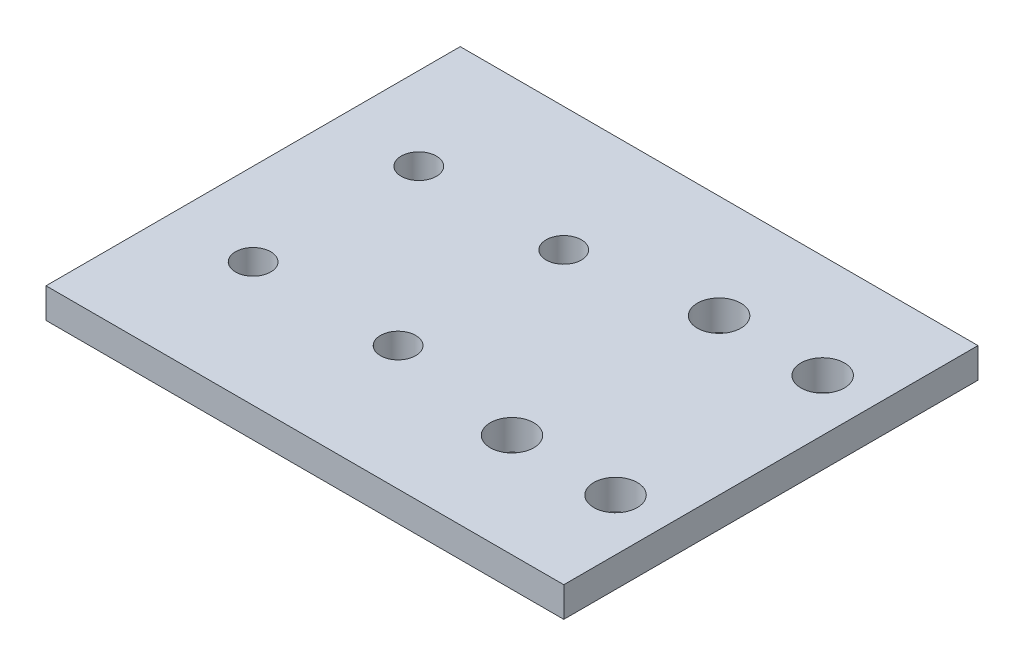
SolidWorks part; units mm, degrees
ref_plane "前视基准面" through (0, 0, 0) normal (0, 0, 1) x (1, 0, 0)
ref_plane "上视基准面" through (0, 0, 0) normal (0, 1, 0) x (1, 0, 0)
ref_plane "右视基准面" through (0, 0, 0) normal (1, 0, 0) x (0, 0, -1)
other "Configuration Table"
sketch "草图1" plane through (0, 0, 0) normal (0, 1, 0) x (1, 0, 0)
  line L0 (0, 120) -> (0, -49880) construction
  line L1 (-100, -120) -> (100, -120)
  line L2 (-100, -120) -> (-100, 120)
  line L3 (-100, 120) -> (100, 120)
  line L4 (100, -120) -> (100, 120)
  line L5 (-100, -120) -> (100, 120) construction
  line L6 (-100, 120) -> (100, -120) construction
  line L7 (-100, 120) -> (-70, 120)
  line L8 (-100, 120) -> (-100, 80)
  line L9 (-100, 80) -> (-70, 80)
  line L10 (-70, 120) -> (-70, 80)
  line L11 (-65, 0) -> (49935, 0) construction
  line L12 (-70, 120) -> (-70, 113)
  line L13 (-70, 113) -> (-70, 87)
  line L14 (-70, 87) -> (-70, 80)
  line L15 (-70, 113) -> (-40, 113)
  line L16 (-40, 113) -> (-40, 87)
  line L17 (-40, 87) -> (-70, 87)
  line L18 (-70, 113) -> (-70, 108)
  line L19 (-70, 87) -> (-70, 92)
  line L20 (-40, 87) -> (-48, 87)
  line L21 (-48, 87) -> (-48, 92)
  line L22 (-48, 92) -> (-40, 92)
  line L23 (-70, 92) -> (-62, 92)
  line L24 (-62, 92) -> (-62, 87)
  line L25 (-70, 100) -> (-40, 100) construction
  line L26 (0, 120) -> (0, 0)
  line L27 (0, 0) -> (-100, 0)
  line L28 (-70, 80) -> (0, 80)
  line L29 (100, 80) -> (70, 80)
  line L30 (70, 120) -> (70, 80)
  line L31 (100, -80) -> (70, -80)
  line L32 (70, -120) -> (70, -80)
  line L33 (-70, -120) -> (-70, -80)
  line L34 (-100, -80) -> (-70, -80)
  line L35 (0, 120) -> (0, 100)
  line L36 (0, 100) -> (-25, 100)
  line L37 (-25, 100) -> (-25, 115)
  line L38 (-25, 100) -> (-25, 85)
  line L39 (-25, 85) -> (-5, 85)
  line L40 (-25, 115) -> (-5, 115)
  line L41 (-5, 115) -> (-5, 85)
  line L42 (5, 115) -> (5, 85)
  line L43 (25, 100) -> (25, 85)
  line L44 (25, 85) -> (5, 85)
  line L45 (25, 115) -> (5, 115)
  line L46 (25, 100) -> (25, 115)
  line L47 (25, -85) -> (5, -85)
  line L48 (25, -100) -> (25, -85)
  line L49 (25, -100) -> (25, -115)
  line L50 (25, -115) -> (5, -115)
  line L51 (5, -115) -> (5, -85)
  line L52 (-25, -100) -> (-25, -115)
  line L53 (-25, -100) -> (-25, -85)
  line L54 (-25, -85) -> (-5, -85)
  line L55 (-5, -115) -> (-5, -85)
  line L56 (-25, -115) -> (-5, -115)
  line L57 (-100, 0) -> (-90, 0)
  line L58 (0, 120) -> (0, 100)
  line L59 (0, 120) -> (0, 110)
  line L60 (-70, 80) -> (0, 80)
  line L61 (-70, 113) -> (-20, 113)
  line L62 (-70, 80) -> (0, 80)
  line L63 (-20, 113) -> (-40, 113)
  line L64 (-20, 113) -> (-20, 87)
  line L65 (-20, 87) -> (-40, 87)
  line L66 (-40, 113) -> (-40, 87)
  line L67 (-20, 87) -> (-20, 80)
  line L68 (-20, 80) -> (-20, 120)
  circle A0 centre (-62, 92) radius 1.7
  circle A1 centre (-48, 92) radius 1.7
  circle A2 centre (-48, 108) radius 1.7
  circle A3 centre (-62, 108) radius 1.7
  circle A4 centre (48, 108) radius 1.7
  circle A5 centre (48, 92) radius 1.7
  circle A6 centre (62, 92) radius 1.7
  circle A7 centre (62, 108) radius 1.7
  circle A8 centre (62, -108) radius 1.7
  circle A9 centre (62, -92) radius 1.7
  circle A10 centre (48, -92) radius 1.7
  circle A11 centre (48, -108) radius 1.7
  circle A12 centre (-48, -92) radius 1.7
  circle A13 centre (-62, -92) radius 1.7
  circle A14 centre (-48, -108) radius 1.7
  circle A15 centre (-62, -108) radius 1.7
  circle A16 centre (-90, 0) radius 2.5
  circle A17 centre (-90, 50) radius 2.5
  circle A18 centre (-90, -50) radius 2.5
  circle A19 centre (90, -50) radius 2.5
  circle A20 centre (90, 0) radius 2.5
  circle A21 centre (90, 50) radius 2.5
  circle A22 centre (0, 110) radius 2.5
  circle A23 centre (35, 110) radius 2.5
  point P0 (0, 0)
  point P11 (0, 120)
  point P14 (-100, 0)
  point P15 (100, 0)
  dimension "D12" = 3.4
  dimension "D13" = 3.4
  dimension "D19" = 5
  dimension "D23" = 5
  dimension "D1" = 200
  dimension "D2" = 240
  dimension "D3" = 30
  dimension "D4" = 40
  dimension "D5" = 7
  dimension "D6" = 7
  dimension "D7" = 30
  dimension "D8" = 5
  dimension "D9" = 5
  dimension "D10" = 8
  dimension "D11" = 8
  dimension "D14" = 25
  dimension "D15" = 15
  dimension "D16" = 15
  dimension "D17" = 20
  dimension "D18" = 10
  dimension "D21" = 20
  dimension "D22" = 10
  dimension "D25" = 50
  dimension "D26" = 40
  dimension "D20" = 2
  dimension "D24" = 2
extrude "凸台-拉伸3" add sketch "草图1" along normal blind 2.9 contours A1 L22 L16 L15 L10 L13 L23 A0 L24 L17 L21 A2 A3 | A0 L23 L10 L17 L24 | A1 L21 L17 L16 L22 | L67 L39 L38 L65 L17 L10 L28 | L65 L38 L37 L61 L16 | L65 L64 L36 L38 | L64 L61 L37 L36 | L67 L65 L38 L39 | L40 L68 L3 L10 L15 L61 L37 | L61 L68 L40 L37
sketch "草图3" plane through (0, 2.9, 0) normal (0, 1, 0) x (1, 0, 0)
  line L0 (-1070, 100) -> (48930, 100)
  line L1 (-70, 120) -> (-70, 80) construction
  line L2 (-20, 100) -> (-20, 110)
  line L3 (-20, 120) -> (-20, 80) construction
  line L4 (-20, 110) -> (-25, 110)
  circle A0 centre (-25, 110) radius 2.1
  circle A1 centre (-25, 90) radius 2.1
  circle A2 centre (-35, 90) radius 2.1
  circle A3 centre (-35, 110) radius 2.1
  point P5 (-70, 100)
  point P13 (0, 0)
  dimension "D3" = 4.2
  dimension "D1" = 10
  dimension "D2" = 5
  dimension "D4" = 2
extrude "切除-拉伸3" cut sketch "草图3" against normal blind 2.9
